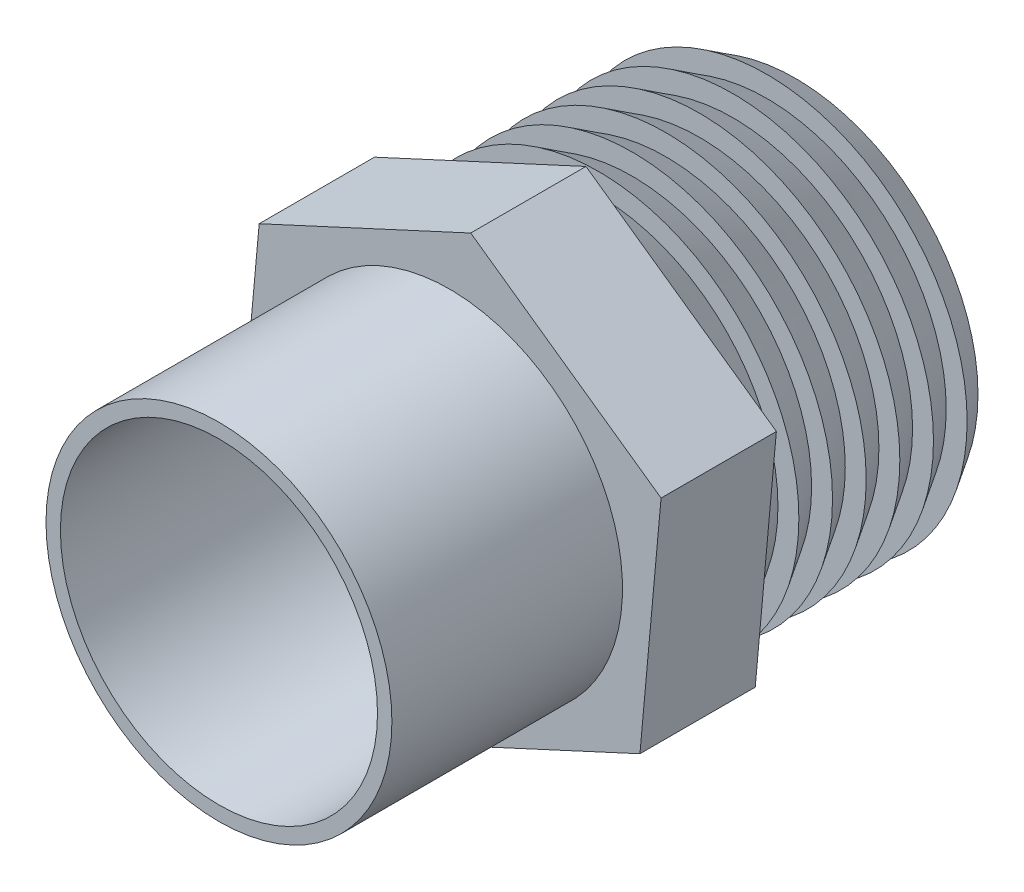
SolidWorks part; units mm, degrees
ref_plane "Front Plane" through (0, 0, 0) normal (0, 0, 1) x (1, 0, 0)
ref_plane "Top Plane" through (0, 0, 0) normal (0, 1, 0) x (1, 0, 0)
ref_plane "Right Plane" through (0, 0, 0) normal (1, 0, 0) x (0, 0, -1)
sketch "Sketch1" plane through (0, 0, 0) normal (0, 0, 1) x (1, 0, 0)
  circle A0 centre (0, 0) radius 9.525
  circle A1 centre (0, 0) radius 8.7312
  dimension "D1" = 19.05
  dimension "D2" = 17.4625
extrude "Boss-Extrude1" add sketch "Sketch1" along normal blind 12.7
sketch "Sketch2" plane through (0, 0, 0) normal (0, 0, -1) x (-1, 0, 0)
  line L1 (-10.4844, -7.3979) -> (1.1645, -12.7787)
  line L2 (1.1645, -12.7787) -> (11.6489, -5.3808)
  line L3 (11.6489, -5.3808) -> (10.4844, 7.3979)
  line L4 (10.4844, 7.3979) -> (-1.1645, 12.7787)
  line L5 (-1.1645, 12.7787) -> (-11.6489, 5.3808)
  line L6 (-11.6489, 5.3808) -> (-10.4844, -7.3979)
  circle A0 centre (0, 0) radius 11.1125 construction
  dimension "D1" = 22.225
extrude "Boss-Extrude2" add sketch "Sketch2" along normal blind 6.35
sketch "Sketch3" plane through (0, 0, 0) normal (1, 0, 0) x (0, 0, -1)
  line L0 (0, 0) -> (6.35, 0)
  line L1 (6.35, 0) -> (6.35, 8.7312)
  line L2 (6.35, 8.7312) -> (19.05, 8.7312)
  line L3 (6.35, 12.7787) -> (6.35, 5.3808) construction
  line L4 (6.35, 8.7312) -> (6.35, 11.0345)
  line L5 (6.35, 11.0345) -> (8.2034, 9.8829)
  line L6 (8.2034, 9.8829) -> (8.2034, 11.0345)
  line L7 (8.2034, 11.0345) -> (10.0568, 9.8829)
  line L8 (10.0568, 9.8829) -> (10.0568, 11.0345)
  line L9 (10.0568, 11.0345) -> (11.9101, 9.8829)
  line L10 (11.9101, 9.8829) -> (11.9101, 11.0345)
  line L11 (11.9101, 11.0345) -> (13.7635, 9.8829)
  line L12 (13.7635, 9.8829) -> (13.7635, 11.0345)
  line L13 (13.7635, 11.0345) -> (15.6169, 9.8829)
  line L14 (15.6169, 9.8829) -> (15.6169, 11.0345)
  line L15 (15.6169, 11.0345) -> (17.4703, 9.8829)
  line L16 (17.4703, 9.8829) -> (17.4703, 11.0345)
  line L17 (17.4703, 11.0345) -> (19.05, 10.0529)
  line L18 (19.05, 10.0529) -> (19.05, 8.7312)
  dimension "D1" = 6.35
  dimension "D2" = 8.7312
  dimension "D3" = 12.7
revolve "Revolve1" add sketch "Sketch3" angle 360 about L0
sketch "Sketch4" plane through (0, 0, 12.7) normal (0, 0, 1) x (1, 0, 0)
  circle A1 centre (0, 0) radius 8.7312
extrude "Cut-Extrude1" cut sketch "Sketch4" against normal through all
